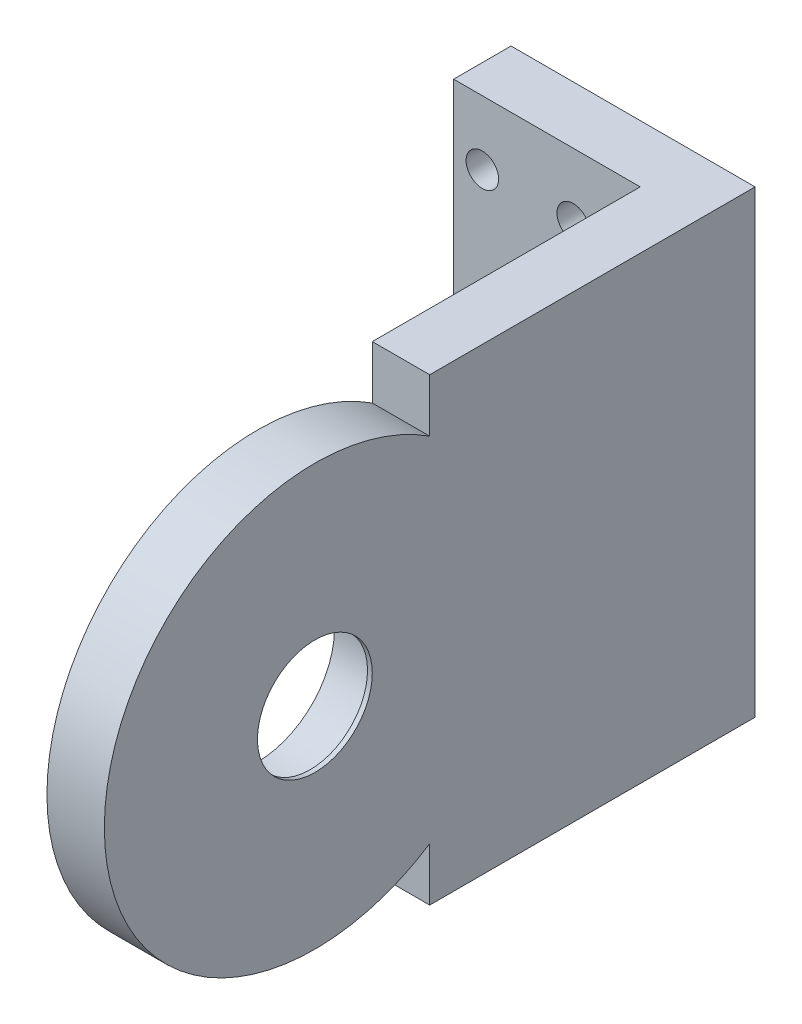
SolidWorks part; units mm, degrees
ref_plane "Front Plane" through (0, 0, 0) normal (0, 0, 1) x (1, 0, 0)
ref_plane "Top Plane" through (0, 0, 0) normal (0, 1, 0) x (1, 0, 0)
ref_plane "Right Plane" through (0, 0, 0) normal (1, 0, 0) x (0, 0, -1)
ref_plane "Plane1" through (336.5, 0, 0) normal (1, 0, 0) x (0, 0, -1)
sketch "Sketch1" plane through (336.5, 0, 0) normal (1, 0, 0) x (0, 0, -1)
  circle A0 centre (-300, 300) radius 22
extrude "Boss-Extrude1" add sketch "Sketch1" along normal blind 6
sketch "Sketch2" plane through (336.5, 0, 0) normal (1, 0, 0) x (0, 0, -1)
  line L0 (-254, 276) -> (-288, 276)
  line L1 (-288, 276) -> (-288, 324)
  line L2 (-288, 324) -> (-254, 324)
  line L3 (-254, 324) -> (-254, 276)
extrude "Boss-Extrude2" add sketch "Sketch2" along normal blind 6
sketch "Sketch3" plane through (336.5, 0, 0) normal (1, 0, 0) x (0, 0, -1)
  circle A0 centre (-300, 300) radius 6
extrude "Cut-Extrude1" cut sketch "Sketch3" along normal blind 6.01
sketch "Sketch4" plane through (336.5, 0, 0) normal (1, 0, 0) x (0, 0, -1)
  circle A0 centre (-300, 300) radius 8.05
extrude "Cut-Extrude2" cut sketch "Sketch4" along normal blind 5.5
ref_plane "Plane2" through (0, 0, 254) normal (0, 0, 1) x (1, 0, 0)
sketch "Sketch5" plane through (0, 0, 254) normal (0, 0, 1) x (1, 0, 0)
  line L0 (317, 276) -> (336.51, 276)
  line L1 (336.51, 276) -> (336.51, 324)
  line L2 (336.51, 324) -> (317, 324)
  line L3 (317, 324) -> (317, 276)
  circle A0 centre (320, 282.7) radius 1.7
  circle A1 centre (320, 317.3) radius 1.7
  circle A2 centre (329.5, 282.7) radius 1.7
  circle A3 centre (329.5, 317.3) radius 1.7
extrude "Boss-Extrude3" add sketch "Sketch5" along normal blind 6
